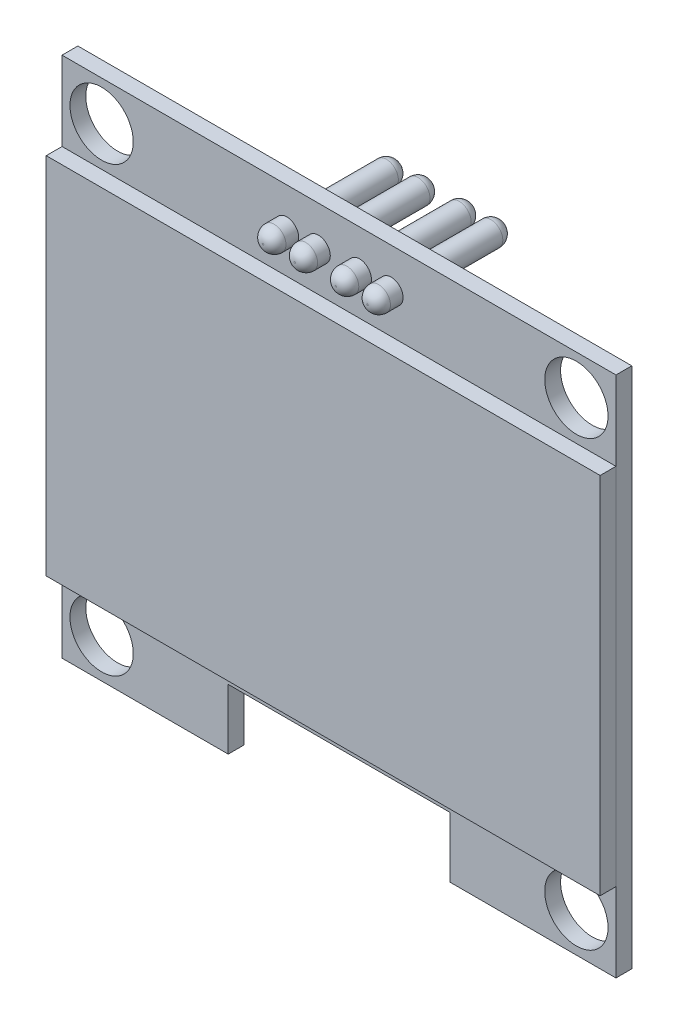
SolidWorks part; units mm, degrees
ref_plane "Front Plane" through (0, 0, 0) normal (0, 0, 1) x (1, 0, 0)
ref_plane "Top Plane" through (0, 0, 0) normal (0, 1, 0) x (1, 0, 0)
ref_plane "Right Plane" through (0, 0, 0) normal (1, 0, 0) x (0, 0, -1)
sketch "Sketch1" plane through (0, 0, 0) normal (0, 0, 1) x (1, 0, 0)
  line L0 (0, 0) -> (0, 16.5) construction
  line L1 (-17.5, -16.5) -> (-7, -16.5)
  line L2 (-17.5, -16.5) -> (-17.5, 16.5)
  line L3 (-17.5, 16.5) -> (17.5, 16.5)
  line L4 (17.5, -16.5) -> (17.5, 16.5)
  line L5 (-17.5, -16.5) -> (17.5, 16.5) construction
  line L6 (-17.5, 16.5) -> (17.5, -16.5) construction
  line L7 (0, 0) -> (17.5, 0) construction
  line L8 (-7, -12.6831) -> (7, -12.6831)
  line L9 (-7, -12.6831) -> (-7, -16.5)
  line L10 (7, -12.6831) -> (7, -16.5)
  line L11 (7, -16.5) -> (17.5, -16.5)
  circle A0 centre (-15, 14) radius 2
  circle A1 centre (15, 14) radius 2
  circle A2 centre (15, -14) radius 2
  circle A3 centre (-15, -14) radius 2
  point P0 (0, 0)
  point P11 (0, -12.6831)
  point P12 (0, 8.25)
  dimension "D4" = 4
  dimension "D1" = 33
  dimension "D2" = 35
  dimension "D3" = 14
  dimension "D5" = 2.5
  dimension "D6" = 2.5
extrude "Boss-Extrude1" add sketch "Sketch1" along normal blind 1
sketch "Sketch2" plane through (0, 0, 1) normal (0, 0, 1) x (1, 0, 0)
  line L1 (-17.5, 11.5) -> (-17.5, -11.5)
  line L2 (17.5, 21.5) -> (-17.5, 21.5)
  line L3 (17.5, 21.5) -> (-17.5, 21.5)
  line L4 (17.5, 11.5) -> (-17.5, 11.5)
  line L5 (17.5, 11.5) -> (-17.5, 11.5)
  line L6 (-17.5, 16.5) -> (-17.5, -16.5) construction
  line L7 (-17.5, -11.5) -> (17.5, -11.5)
  line L8 (17.5, -16.5) -> (17.5, 16.5) construction
  line L9 (17.5, -11.5) -> (17.5, 11.5)
  line M4 (17.5, -16.5) -> (17.5, 16.5)
  line M6 (-17.5, 16.5) -> (-17.5, -16.5)
  dimension "D3" = 23
  dimension "D1" = 5
  dimension "D2" = 5
extrude "Boss-Extrude2" add sketch "Sketch2" along normal blind 1 separate body contours L7 L5 M6 M4
sketch "Sketch3" plane through (0, 0, 2) normal (0, 0, 1) x (1, 0, 0)
  line L0 (0, 0) -> (0, 16.5) construction
  line L1 (17.5, 16.5) -> (-17.5, 16.5) construction
  line L2 (-15, 14) -> (15, 14) construction
  circle A0 centre (-1.3, 14) radius 0.75
  circle A1 centre (-3.3, 14) radius 0.75
  circle A2 centre (1.3, 14) radius 0.75
  circle A3 centre (3.3, 14) radius 0.75
  point P13 (0, 0)
  dimension "D1" = 1.5
  dimension "D2" = 1.3
  dimension "D3" = 2
extrude "Boss-Extrude3" add sketch "Sketch3" along normal blind 0.5 and the other way blind 8
fillet "Fillet1" radius 0.7 8 edges at (2.55, 14, 2.5) (0.55, 14, 2.5) (-0.55, 14, 2.5) (-2.55, 14, 2.5) (2.55, 14, -6) (0.55, 14, -6) (-0.55, 14, -6) (-2.55, 14, -6)
